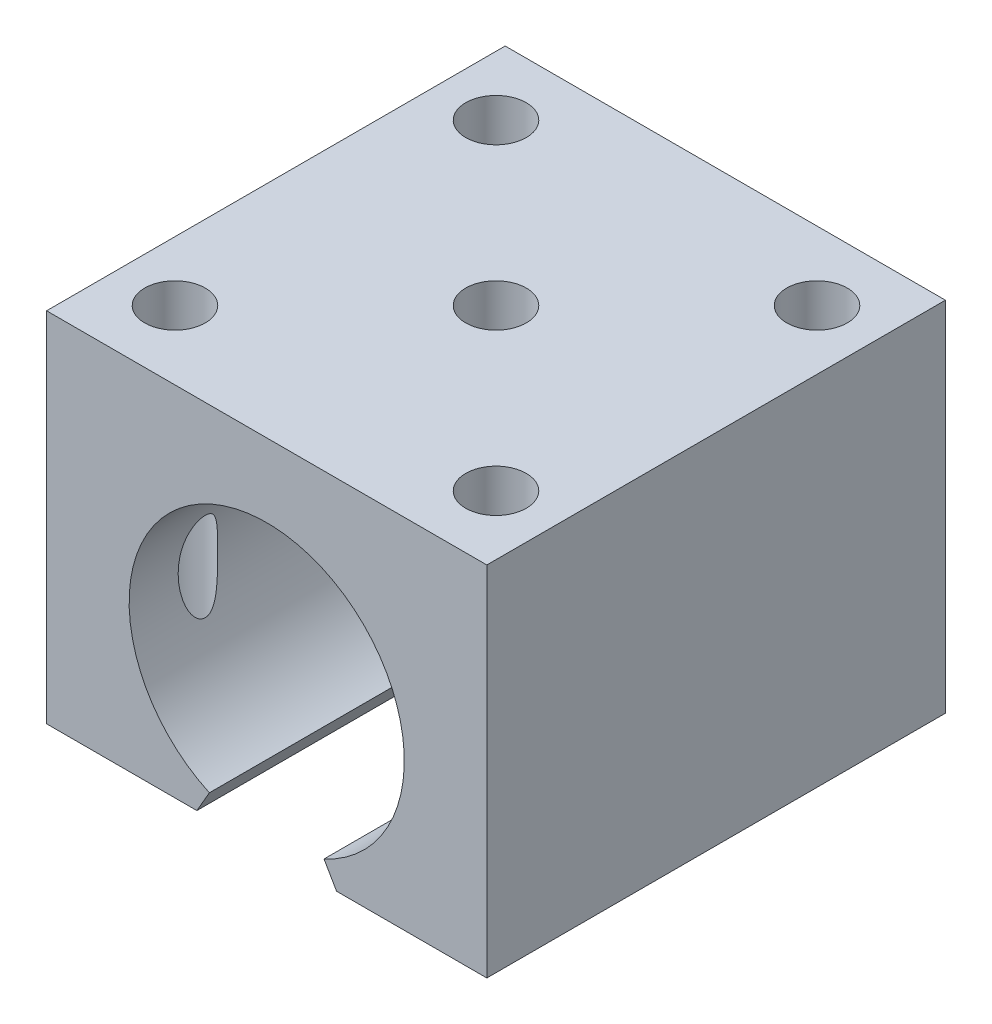
SolidWorks part; units mm, degrees
ref_plane "Front Plane" through (0, 0, 0) normal (0, 0, 1) x (1, 0, 0)
ref_plane "Top Plane" through (0, 0, 0) normal (0, 1, 0) x (1, 0, 0)
ref_plane "Right Plane" through (0, 0, 0) normal (1, 0, 0) x (0, 0, -1)
sketch "Sketch1" plane through (0, 0, 0) normal (0, 1, 0) x (1, 0, 0)
  line L1 (0, 0) -> (48, 0)
  line L2 (0, 0) -> (0, 50)
  line L3 (0, 50) -> (48, 50)
  line L4 (48, 0) -> (48, 50)
  line L5 (0, 0) -> (48, 50) construction
  line L6 (0, 50) -> (48, 0) construction
  point P4 (24, 25)
  dimension "D1" = 48
  dimension "D2" = 50
extrude "Boss-Extrude1" add sketch "Sketch1" along normal blind 39
hole_wizard "M6 Clearance Hole1" positions "Sketch2" profile "Sketch3" hole size "M6" standard "ANSI Metric" end condition through all
sketch "Sketch2" plane through (0, 39, 0) normal (0, 1, 0) x (1, 0, 0)
  line L1 (6.5, 7.5) -> (41.5, 7.5)
  line L2 (6.5, 7.5) -> (6.5, 42.5)
  line L3 (6.5, 42.5) -> (41.5, 42.5)
  line L4 (41.5, 7.5) -> (41.5, 42.5)
  line L5 (6.5, 7.5) -> (41.5, 42.5) construction
  line L6 (6.5, 42.5) -> (41.5, 7.5) construction
  line L7 (48, 50) -> (0, 50) construction
  line L8 (48, 0) -> (48, 50) construction
  point P0 (6.5, 42.5)
  point P2 (41.5, 42.5)
  point P4 (41.5, 7.5)
  point P6 (6.5, 7.5)
  point P47 (24, 25)
  point P49 (0, 0)
  point P52 (24, 50)
  point P55 (48, 25)
  point P56 (41.5, 7.5)
  point P57 (6.5, 42.5)
  dimension "D1" = 35
sketch "Sketch3" plane through (6.5, 39, -42.5) normal (1, 0, 0) x (0, 0, 1)
  line L0 (0, 0) -> (0, 39)
  line L1 (0, 39) -> (3.3, 39)
  line L2 (3.3, 39) -> (3.3, 0)
  line L5 (3.3, 0) -> (0, 0)
  line L11 (0, -6.35) -> (0, 107.95) construction
  dimension "Thru Hole Dia." = 6.6
  dimension "Thru Hole Depth" = 39
sketch "Sketch4" plane through (0, 0, 0) normal (0, 0, 1) x (1, 0, 0)
  line L0 (17.75, 2.3641) -> (24, 13.1894) construction
  line L1 (24, 13.1894) -> (30.25, 2.3641) construction
  line L2 (0, 39) -> (48, 39) construction
  line L3 (30.25, 2.3641) -> (31.6149, 0)
  line L4 (0, 0) -> (48, 0) construction
  line L5 (31.6149, 0) -> (16.3851, 0)
  line L6 (16.3851, 0) -> (17.75, 2.3641)
  arc A0 (30.25, 2.3641) -> (17.75, 2.3641) centre (24, 16) ccw
  arc A1 (17.75, 2.3641) -> (30.25, 2.3641) centre (24, 16) ccw construction
  point P12 (24, 39)
  dimension "D1" = 30
  dimension "D2" = 23
  dimension "D3" = 60
  dimension "D4" = 12.5
extrude "Cut-Extrude1" cut sketch "Sketch4" against normal through all
